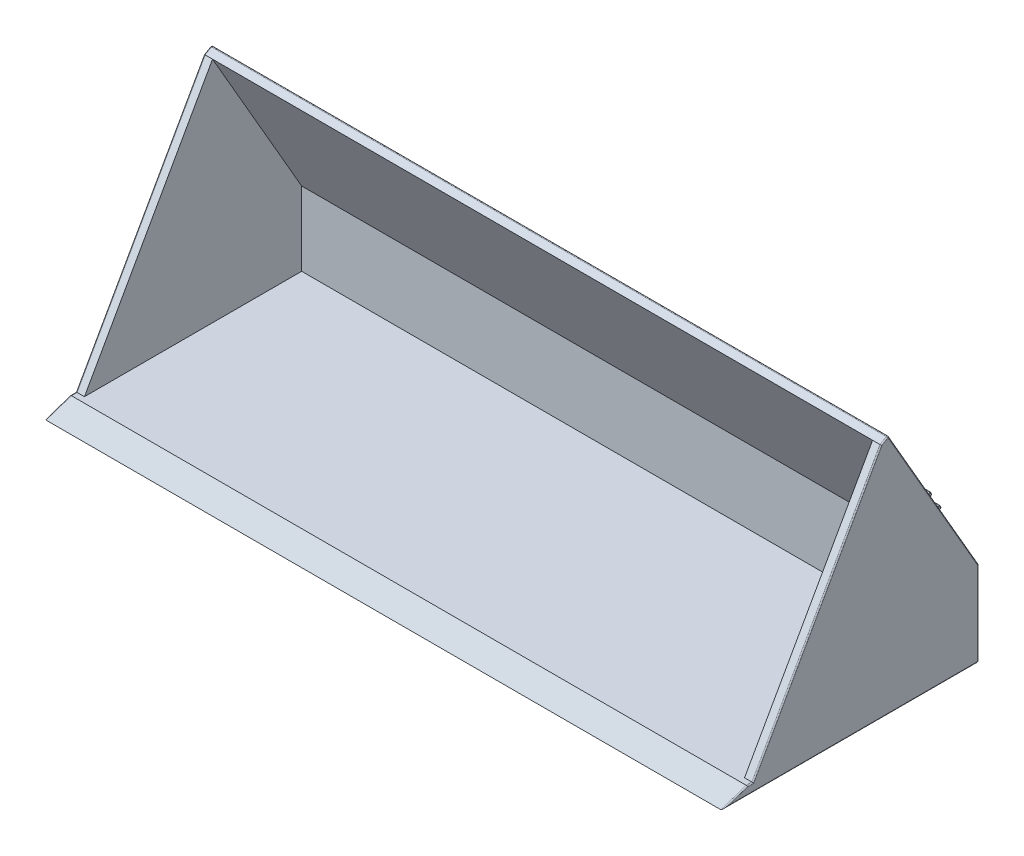
SolidWorks part; units mm, degrees
ref_plane "前视基准面" through (0, 0, 0) normal (0, 0, 1) x (1, 0, 0)
ref_plane "上视基准面" through (0, 0, 0) normal (0, 1, 0) x (1, 0, 0)
ref_plane "右视基准面" through (0, 0, 0) normal (1, 0, 0) x (0, 0, -1)
sketch "草图1" plane through (0, 0, 0) normal (1, 0, 0) x (0, 0, -1)
  line L0 (0, 0) -> (-40, 0)
  line L1 (0, 0) -> (0, 15)
  line L2 (0, 15) -> (-16, 42.7128)
  line L3 (-1.5, 1.5) -> (-40, 1.5)
  line L4 (-1.5, 1.5) -> (-1.5, 14.5981)
  line L5 (-1.5, 14.5981) -> (-17.299, 41.9628)
  line L6 (-16, 42.7128) -> (-17.299, 41.9628)
  line L7 (-40, 0) -> (-45.5, 0)
  line L8 (-45.5, 0) -> (-41, 1.5)
  line L9 (-41, 1.5) -> (-40, 1.5)
  dimension "D1" = 40
  dimension "D2" = 15
  dimension "D3" = 150
  dimension "D4" = 32
  dimension "D5" = 1.5
  dimension "D6" = 5.5
  dimension "D7" = 1
extrude "凸台-拉伸1" add sketch "草图1" along normal blind 117
sketch "草图2" plane through (117, 0, 0) normal (1, 0, 0) x (0, 0, -1)
  line L0 (-41, 1.5) -> (-40, 1.5)
  line L1 (-1.5, 1.5) -> (-41, 1.5) construction
  line L2 (-17.299, 41.9628) -> (-40, 1.5)
  line L8 (0, 0) -> (0, 15)
  line L9 (0, 15) -> (-16, 42.7128)
  line L10 (-16, 42.7128) -> (-17.299, 41.9628)
  line L11 (-17.299, 41.9628) -> (-1.5, 14.5981)
  line L12 (-1.5, 14.5981) -> (-1.5, 1.5)
  line L13 (-1.5, 1.5) -> (-41, 1.5)
  line L14 (-41, 1.5) -> (-45.5, 0)
  line L15 (-45.5, 0) -> (0, 0)
  line L16 (0, 0) -> (0, 15)
  line L17 (0, 15) -> (-16, 42.7128)
  line L18 (-16, 42.7128) -> (-17.299, 41.9628)
  line L22 (-41, 1.5) -> (-45.5, 0)
  line L23 (-45.5, 0) -> (0, 0)
  dimension "D2" = 1
  dimension "D1" = 0
extrude "凸台-拉伸2" add sketch "草图2" along normal blind 1.5
sketch "草图3" plane through (0, 0, 0) normal (-1, 0, 0) x (0, 0, 1)
  line L16 (41, 1.5) -> (40, 1.5)
  line L17 (17.299, 41.9628) -> (40, 1.5)
  line L24 (0, 15) -> (0, 0)
  line L25 (0, 0) -> (45.5, 0)
  line L26 (45.5, 0) -> (41, 1.5)
  line L27 (41, 1.5) -> (1.5, 1.5)
  line L28 (1.5, 1.5) -> (1.5, 14.5981)
  line L29 (1.5, 14.5981) -> (17.299, 41.9628)
  line L30 (17.299, 41.9628) -> (16, 42.7128)
  line L31 (16, 42.7128) -> (0, 15)
  line L32 (0, 15) -> (0, 0)
  line L33 (0, 0) -> (45.5, 0)
  line L34 (45.5, 0) -> (41, 1.5)
  line L38 (17.299, 41.9628) -> (16, 42.7128)
  line L39 (16, 42.7128) -> (0, 15)
  dimension "D1" = 0
extrude "凸台-拉伸3" add sketch "草图3" along normal blind 1.5
sketch "草图4" plane through (-1.5, 0, 0) normal (-1, 0, 0) x (0, 0, 1)
  line L0 (0, 0) -> (0, 7.5) construction
  line L1 (0, 15) -> (0, 0) construction
  line L2 (0, 7.5) -> (-2, 7.5) construction
  line L3 (-2, 7.5) -> (-2.5, 7.5) construction
  line L4 (0, 7.5) -> (0, 6)
  line L5 (0, 6) -> (-0.6771, 6)
  line L6 (-2.5, 6.0566) -> (-2.5, 5.55)
  line L7 (-2.5, 5.55) -> (-1.5556, 5.55)
  line L8 (0, 7.5) -> (-2.5, 6.0566)
  arc A0 (-1.5556, 5.55) -> (-0.6771, 6) centre (-2, 7.5) ccw
  dimension "D5" = 2
  dimension "D1" = 2
  dimension "D2" = 0.5
  dimension "D3" = 1.5
  dimension "D4" = 1.95
  dimension "D6" = 30
extrude "凸台-拉伸4" add sketch "草图4" against normal blind 108 from offset 6 offset against normal yes
ref_plane "基准面1" through (0, 7.5, 0) normal (0, -1, 0) x (-1, 0, 0)
mirror "镜向1" about plane through (0, 7.5, 0) normal (0, -1, 0) of "凸台-拉伸4"
sketch "草图5" plane through (-1.5, 0, 0) normal (-1, 0, 0) x (0, 0, 1)
  line L0 (0, 15) -> (3.75, 21.4952) construction
  line L1 (16, 42.7128) -> (0, 15) construction
  line L2 (3.75, 21.4952) -> (2.0179, 22.4952) construction
  line L3 (2.0179, 22.4952) -> (1.5849, 22.7452) construction
  line L4 (3.75, 21.4952) -> (4.5, 22.7942)
  line L5 (4.5, 22.7942) -> (3.9136, 23.1328)
  line L6 (2.3066, 23.9952) -> (2.5599, 24.4339)
  line L7 (2.5599, 24.4339) -> (3.3778, 23.9617)
  line L8 (3.75, 21.4952) -> (2.3066, 23.9952)
  arc A0 (3.9136, 23.1328) -> (3.3778, 23.9617) centre (2.0179, 22.4952) ccw
  dimension "D7" = 2
  dimension "D1" = 7.5
  dimension "D2" = 2
  dimension "D3" = 0.5
  dimension "D4" = 1.5
  dimension "D5" = 90
  dimension "D6" = 1.95
  dimension "D8" = 30
extrude "凸台-拉伸5" add sketch "草图5" against normal blind 108 from offset 6 offset against normal yes
ref_plane "基准面2" through (0, 17.7452, 10.2452) normal (0, 0.866, 0.5) x (1, 0, 0)
mirror "镜向2" about plane through (0, 17.7452, 10.2452) normal (0, 0.866, 0.5) of "凸台-拉伸5"
fillet "圆角1" radius 0.1 16 edges at (58.5, 5.55, -2.5) (112.5, 5.8033, -2.5) (58.5, 6.0566, -2.5) (4.5, 5.8033, -2.5) (58.5, 8.9434, -2.5) (112.5, 9.1967, -2.5) (58.5, 9.45, -2.5) (4.5, 9.1967, -2.5) (58.5, 21.0564, 0.6099) (112.5, 21.2758, 0.7366) (58.5, 21.4952, 0.8632) (4.5, 21.2758, 0.7366) (58.5, 23.9952, 2.3066) (112.5, 24.2146, 2.4333) (58.5, 24.4339, 2.5599) (4.5, 24.2146, 2.4333)
fillet "圆角2" radius 0.2 17 edges at (118.5, 0.75, 43.25) (118.5, 1.5, 40.5) (118.5, 21.7314, 28.6495) (118.5, 42.3378, 16.6495) (118.5, 28.8564, 8) (118.5, 7.5, 0) (118.5, 0, 22.75) (-1.5, 42.3378, 16.6495) (-1.5, 21.7314, 28.6495) (-1.5, 1.5, 40.5) (-1.5, 0.75, 43.25) (-1.5, 0, 22.75) (-1.5, 7.5, 0) (-1.5, 28.8564, 8) (58.5, 0, 0) (58.5, 15, 0) (58.5, 42.7128, 16)
